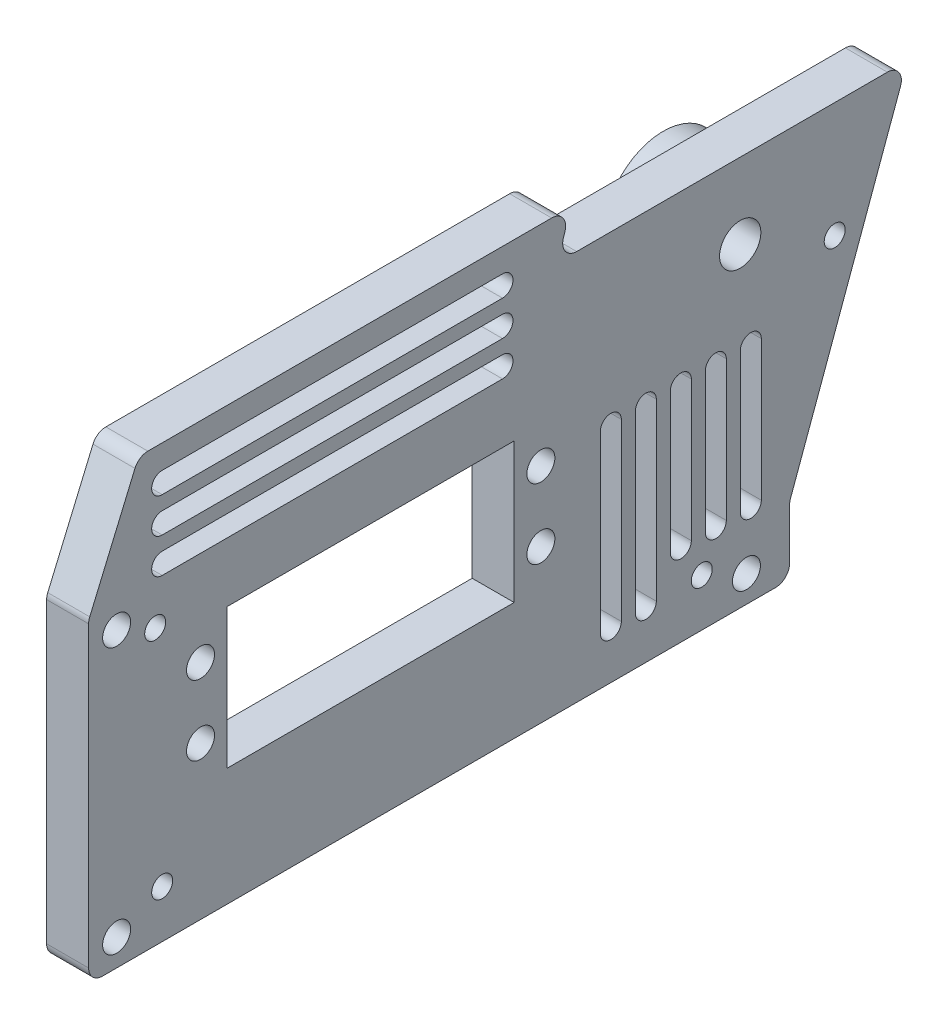
SolidWorks part; units mm, degrees
ref_plane "前视基准面" through (0, 0, 0) normal (0, 0, 1) x (1, 0, 0)
ref_plane "上视基准面" through (0, 0, 0) normal (0, 1, 0) x (1, 0, 0)
ref_plane "右视基准面" through (0, 0, 0) normal (1, 0, 0) x (0, 0, -1)
sketch "草图1" plane through (0, 0, 0) normal (1, 0, 0) x (0, 0, -1)
  line L33 (-58.1085, -35) -> (42.0593, -35)
  line L34 (42.0593, -35) -> (42.0593, -30.6775)
  line L35 (-58.1085, 10) -> (-50.9678, 26.7336)
  line L46 (-58.1085, 10) -> (-58.1085, -35)
  line L47 (-50.9678, 26.7336) -> (-8.1085, 26.7336)
  line L50 (10.8022, 26.7336) -> (-8.1085, 26.7336)
  line L56 (10.8022, 26.7336) -> (8.8845, 20.7944)
  line L57 (53.8845, 20.7944) -> (8.8845, 20.7944)
  line L59 (53.8845, 20.7944) -> (58.8845, 20.7944)
  line L60 (58.8845, 20.7944) -> (52.2202, 2.5021)
  line L61 (52.2202, 2.5021) -> (42.0593, -25.3878)
  line L62 (42.0593, -25.3878) -> (42.0593, -30.6775)
  dimension "D1" = 100.1678
  dimension "D2" = 5
extrude "凸台-拉伸1" add sketch "草图1" along normal blind 6
sketch "草图2" plane through (0, 0, 0) normal (1, 0, 0) x (0, 0, -1)
  line L0 (-17.8023, 6.0643) -> (-17.8023, -21.9388) construction
  line L1 (35, 10) -> (-7.8023, -8.1717) construction
  line L2 (-58.1085, -35) -> (42.0593, -35) construction
  line L4 (-17.8023, 1.8283) -> (-38.3023, 1.8283)
  line L9 (-38.3023, 1.8283) -> (-38.3023, -18.1717)
  line L10 (-38.3023, -18.1717) -> (-17.8023, -18.1717)
  line L11 (-17.8023, -18.1717) -> (2.6977, -18.1717)
  line L12 (2.6977, -18.1717) -> (2.6977, 1.8283)
  line L13 (2.6977, 1.8283) -> (-17.8023, 1.8283)
  circle A1 centre (35, 10) radius 2.5 construction
  circle A6 centre (6.5127, -3.1717) radius 2
  circle A7 centre (6.5127, -13.1717) radius 2
  circle A8 centre (-42.1173, -13.1717) radius 2
  circle A9 centre (-42.1173, -3.1717) radius 2
  dimension "D2" = 10
  dimension "D1" = 5
  dimension "D10" = 45
  dimension "D12" = 4
  dimension "D11" = 4
  dimension "D3" = 46.5
  dimension "D4" = 20.5
  dimension "D13" = 20.5
extrude "切除-拉伸1" cut sketch "草图2" along normal blind 10
sketch "草图4" plane through (6, 0, 0) normal (1, 0, 0) x (0, 0, -1)
  line L0 (6.5127, -3.1717) -> (6.5127, 6.8283) construction
  line L3 (-48.5978, 4.3283) -> (48.5022, 4.3283) construction
  line L6 (35, 15) -> (25, 15) construction
  line L7 (35, 15) -> (49, 15) construction
  line L9 (35, 5) -> (21, 5) construction
  line L10 (35, 5) -> (45, 5) construction
  line L11 (49, 15) -> (45, 5) construction
  circle A10 centre (35, 10) radius 2.5 construction
  circle A17 centre (-48.5978, 4.3283) radius 1.5
  circle A19 centre (48.5022, 4.3283) radius 1.5
  dimension "D4" = 3
  dimension "D5" = 5
  dimension "D2" = 97.1
  dimension "D3" = 3
  dimension "D8" = 5
  dimension "D9" = 14
  dimension "D1" = 10
  dimension "D6" = 10
  dimension "D7" = 14
  dimension "D10" = 10
extrude "切除-拉伸2" cut sketch "草图4" against normal blind 6
sketch "草图5" plane through (6, 0, 0) normal (1, 0, 0) x (0, 0, -1)
  circle A1 centre (35, 10) radius 8.5
  dimension "D2" = 17
sketch "草图7" plane through (6, 0, 0) normal (1, 0, 0) x (0, 0, -1)
  line L0 (-47.5978, 6.8283) -> (-47.5978, -28.1717)
  line L1 (-58.1085, 6.8283) -> (-54.1085, 6.8283)
  line L2 (-58.1085, 10) -> (-58.1085, -35) construction
  line L3 (-54.1085, 6.8283) -> (-54.1085, -31.1717)
  line L4 (-54.1085, -31.1717) -> (35.8915, -31.1717)
  line L5 (6.5127, -3.1717) -> (16.5127, -3.1717) construction
  line L6 (16.5127, -3.1717) -> (16.5127, -28.1717) construction
  line L7 (-47.5978, 18.3283) -> (1.0322, 18.3283)
  line L8 (-47.5978, 23.3283) -> (1.0322, 23.3283)
  line L9 (-47.5978, 20.3283) -> (1.0322, 20.3283)
  line L10 (-47.5978, 15.3283) -> (1.0322, 15.3283)
  line L11 (-47.5978, 13.3283) -> (1.0322, 13.3283)
  line L12 (-47.5978, 10.3283) -> (1.0322, 10.3283)
  line L13 (-23.2828, 28.3114) -> (-23.2828, 6.1847) construction
  line L14 (16.5127, -3.1717) -> (21.5127, -3.1717) construction
  line L15 (21.5127, -3.1717) -> (26.5127, -3.1717) construction
  line L16 (26.5127, -3.1717) -> (31.5127, -3.1717) construction
  line L17 (12.7048, -15.6717) -> (36.6303, -15.6717) construction
  line L18 (15.0127, -3.1717) -> (15.0127, -28.1717)
  line L19 (18.0127, -3.1717) -> (18.0127, -28.1717)
  line L20 (20.0127, -3.1717) -> (20.0127, -28.1717)
  line L21 (23.0127, -3.1717) -> (23.0127, -28.1717)
  line L26 (31.5127, -3.1717) -> (36.5127, -3.1717) construction
  line L27 (36.5127, -3.1717) -> (36.5127, -23.1717) construction
  line L28 (35.0127, -3.1717) -> (35.0127, -23.1717)
  line L29 (38.0127, -23.1717) -> (38.0127, -3.1717)
  line L30 (-47.5978, -28.1717) -> (29.5022, -28.1717) construction
  line L31 (35.0127, -23.1717) -> (25.0127, -23.1717) construction
  line L32 (25.0127, -3.1717) -> (25.0127, -23.1717)
  line L33 (28.0127, -3.1717) -> (28.0127, -23.1717)
  line L34 (30.0127, -3.1717) -> (30.0127, -23.1717)
  line L35 (33.0127, -3.1717) -> (33.0127, -23.1717)
  circle A0 centre (-47.5978, -28.1717) radius 1.5
  arc A9 (-47.5978, 23.3283) -> (-47.5978, 20.3283) centre (-47.5978, 21.8283) ccw
  arc A10 (-47.5978, 10.3283) -> (-47.5978, 13.3283) centre (-47.5978, 11.8283) cw
  arc A11 (-47.5978, 18.3283) -> (-47.5978, 15.3283) centre (-47.5978, 16.8283) ccw
  arc A12 (1.0322, 10.3283) -> (1.0322, 13.3283) centre (1.0322, 11.8283) ccw
  arc A13 (1.0322, 18.3283) -> (1.0322, 15.3283) centre (1.0322, 16.8283) cw
  arc A14 (1.0322, 23.3283) -> (1.0322, 20.3283) centre (1.0322, 21.8283) cw
  circle A15 centre (-54.1085, 6.8283) radius 2
  circle A16 centre (-54.1085, -31.1717) radius 2
  circle A17 centre (35.8915, -31.1717) radius 2
  circle A18 centre (16.5127, -3.1717) radius 1.5 construction
  circle A19 centre (21.5127, -3.1717) radius 1.5 construction
  circle A20 centre (26.5127, -3.1717) radius 1.5 construction
  circle A21 centre (31.5127, -3.1717) radius 1.5 construction
  arc A22 (18.0127, -3.1717) -> (15.0127, -3.1717) centre (16.5127, -3.1717) ccw
  arc A23 (20.0127, -3.1717) -> (23.0127, -3.1717) centre (21.5127, -3.1717) cw
  arc A24 (25.0127, -3.1717) -> (28.0127, -3.1717) centre (26.5127, -3.1717) cw
  arc A25 (30.0127, -3.1717) -> (33.0127, -3.1717) centre (31.5127, -3.1717) cw
  arc A28 (20.0127, -28.1717) -> (23.0127, -28.1717) centre (21.5127, -28.1717) ccw
  arc A29 (18.0127, -28.1717) -> (15.0127, -28.1717) centre (16.5127, -28.1717) cw
  circle A30 centre (36.5127, -3.1717) radius 1.5 construction
  circle A31 centre (36.5127, -23.1717) radius 1.5 construction
  arc A32 (35.0127, -3.1717) -> (38.0127, -3.1717) centre (36.5127, -3.1717) cw
  arc A33 (38.0127, -23.1717) -> (35.0127, -23.1717) centre (36.5127, -23.1717) cw
  arc A34 (25.0127, -23.1717) -> (28.0127, -23.1717) centre (26.5127, -23.1717) ccw
  arc A35 (30.0127, -23.1717) -> (33.0127, -23.1717) centre (31.5127, -23.1717) ccw
  circle A36 centre (29.5022, -28.1717) radius 1.5
  point P63 (30.0127, -15.6717)
  point P69 (33.0127, -15.6717)
  point P70 (28.0127, -15.6717)
  point P71 (25.0127, -15.6717)
  point P73 (23.0127, -15.6717)
  point P75 (20.0127, -15.6717)
  point P76 (18.0127, -15.6717)
  point P77 (15.0127, -15.6717)
  dimension "D3" = 3
  dimension "D11" = 4
  dimension "D12" = 38
  dimension "D13" = 4
  dimension "D14" = 90
  dimension "D15" = 4
  dimension "D16" = 5
  dimension "D17" = 5
  dimension "D18" = 3
  dimension "D19" = 3
  dimension "D20" = 3
  dimension "D21" = 3
  dimension "D22" = 5
  dimension "D23" = 3
  dimension "D25" = 3
  dimension "D26" = 77.1
  dimension "D27" = 3
  dimension "D1" = 35
  dimension "D5" = 5
  dimension "D6" = 4
  dimension "D7" = 5
  dimension "D8" = 5
  dimension "D9" = 10
  dimension "D10" = 5
  dimension "D24" = 20
extrude "切除-拉伸3" cut sketch "草图7" against normal blind 6
extrude "凸台-拉伸4" add sketch "草图5" against normal blind 11
fillet "圆角1" radius 2 8 edges at (3, 10, 58.1085) (3, -35, 58.1085) (3, -35, -42.0593) (3, -25.3878, -42.0593) (3, 20.7944, -58.8845) (3, 20.7944, -8.8845) (3, 26.7336, -10.8022) (3, 26.7336, 50.9678)
sketch "草图8" plane through (-5, 0, 0) normal (-1, 0, 0) x (0, 0, 1)
  circle A0 centre (-35, 10) radius 7.55
  dimension "D1" = 15.1
extrude "切除-拉伸4" cut sketch "草图8" against normal blind 5
sketch "草图9" plane through (0, 0, 0) normal (-1, 0, 0) x (0, 0, 1)
  circle A0 centre (-35, 10) radius 2.95
  dimension "D1" = 5.9
extrude "切除-拉伸5" cut sketch "草图9" against normal blind 6
